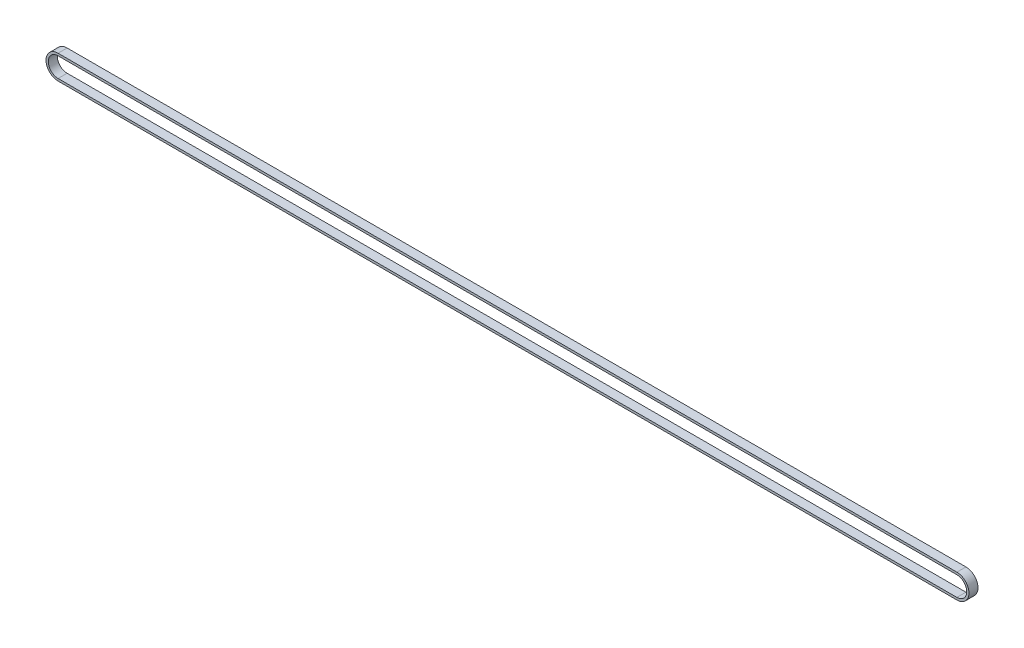
SolidWorks part; units mm, degrees
material "Rubber"
ref_plane "Front Plane" through (0, 0, 0) normal (0, 0, 1) x (1, 0, 0)
ref_plane "Top Plane" through (0, 0, 0) normal (0, 1, 0) x (1, 0, 0)
ref_plane "Right Plane" through (0, 0, 0) normal (1, 0, 0) x (0, 0, -1)
sketch "Sketch1" plane through (0, 0, 0) normal (0, 0, 1) x (1, 0, 0)
  line L0 (298, 0) -> (-298, 0)
  line L4 (-298, -14) -> (298, -14)
  arc A0 (-298, 0) -> (-298, -14) centre (-298, -7) ccw
  arc A1 (298, -14) -> (298, 0) centre (298, -7) ccw
  dimension "D1" = 7
  dimension "D2" = 596
extrude "Extrude-Thin1" add sketch "Sketch1" along normal mid plane 6 thin
